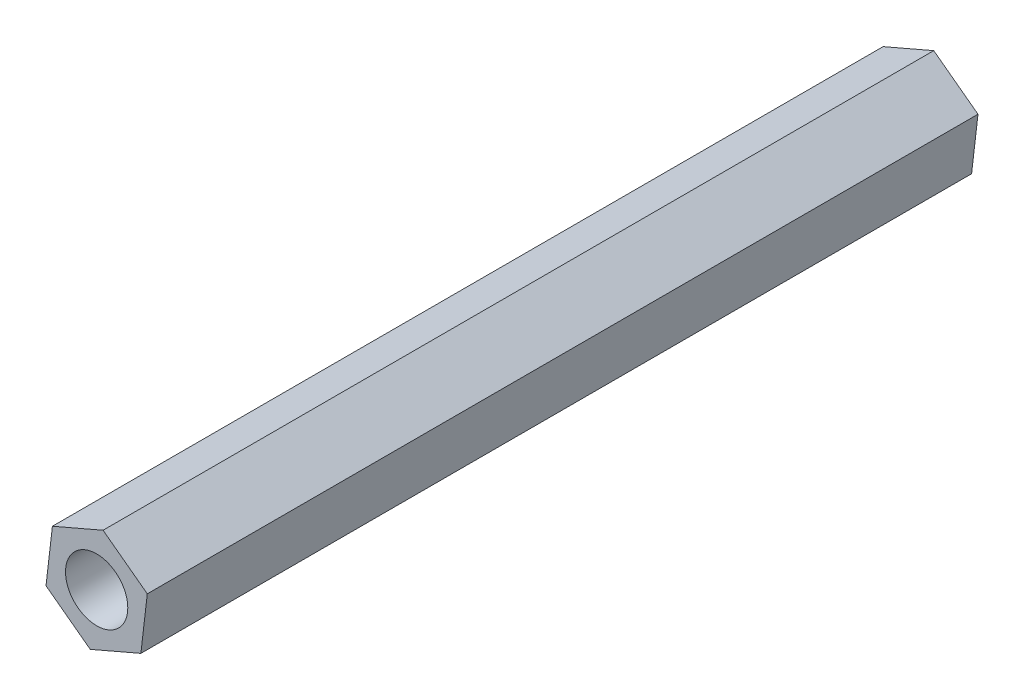
SolidWorks part; units mm, degrees
ref_plane "前视基准面" through (0, 0, 0) normal (0, 0, 1) x (1, 0, 0)
ref_plane "上视基准面" through (0, 0, 0) normal (0, 1, 0) x (1, 0, 0)
ref_plane "右视基准面" through (0, 0, 0) normal (1, 0, 0) x (0, 0, -1)
sketch "草图1" plane through (0, 0, 0) normal (0, 0, 1) x (1, 0, 0)
  line L1 (2.1302, -1.5861) -> (2.4387, 1.0517)
  line L2 (2.4387, 1.0517) -> (0.3085, 2.6378)
  line L3 (0.3085, 2.6378) -> (-2.1302, 1.5861)
  line L4 (-2.1302, 1.5861) -> (-2.4387, -1.0517)
  line L5 (-2.4387, -1.0517) -> (-0.3085, -2.6378)
  line L6 (-0.3085, -2.6378) -> (2.1302, -1.5861)
  circle A0 centre (0, 0) radius 2.3 construction
  dimension "D1" = 4.6
extrude "凸台-拉伸2" add sketch "草图1" along normal blind 40
sketch "草图3" plane through (0, 0, 40) normal (0, 0, 1) x (1, 0, 0)
  circle A0 centre (0, 0) radius 1.5
extrude "切除-拉伸1" cut sketch "草图3" against normal through all
